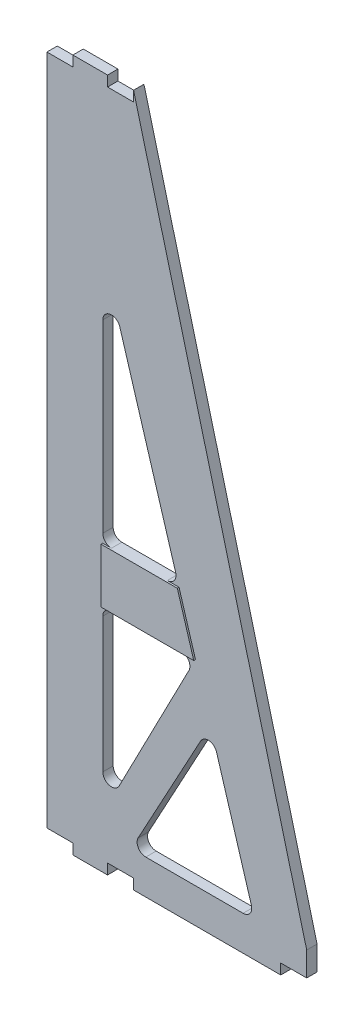
SolidWorks part; units mm, degrees
ref_plane "Plano frontal" through (0, 0, 0) normal (0, 0, 1) x (1, 0, 0)
ref_plane "Plano superior" through (0, 0, 0) normal (0, 1, 0) x (1, 0, 0)
ref_plane "Plano direito" through (0, 0, 0) normal (1, 0, 0) x (0, 0, -1)
sketch "Esboço2" plane through (0, 0, 0) normal (0, 0, 1) x (1, 0, 0)
  line L0 (0, 0) -> (0, 400)
  line L1 (0, 0) -> (150, 0)
  line L2 (150, 0) -> (150, 20)
  line L3 (0, 400) -> (50, 400)
  line L4 (50, 400) -> (150, 20)
extrude "Ressalto-extrusão1" add sketch "Esboço2" along normal blind 6
sketch "Esboço7" plane through (0, 0, 0) normal (0, 0, -1) x (-1, 0, 0)
  line L0 (-150, 20) -> (-120, 20) construction
  line L1 (-150, 0) -> (-150, 20) construction
  line L2 (-150, 20) -> (-50, 400) construction
  line L3 (0, 20) -> (-32.2764, 20) construction
  line L4 (0, 400) -> (0, 0) construction
  line L5 (-32.2764, 400) -> (-32.2764, 310) construction
  line L6 (-50, 400) -> (0, 400) construction
  line L7 (-32.2764, 20) -> (-32.2764, 310)
  line L8 (-120, 20) -> (-32.2764, 310)
  line L9 (-120, 20) -> (-32.2764, 20)
extrude "Corte-extrusão1" cut sketch "Esboço7" against normal through all
fillet "Filete1" radius 5 3 edges at (32.2764, 310, 3) (32.2764, 20, 3) (120, 20, 3)
ref_plane "Plano1" through (150, 0, 0) normal (1, 0, 0) x (0, 0, -1)
sketch "Esboço11" plane through (0, 0, 0) normal (0, 0, -1) x (-1, 0, 0)
  line L0 (-85.7903, 133.0918) -> (-32.2764, 133.0918)
  line L1 (-42.0622, 277.6496) -> (-118.0496, 26.4477) construction
  line L2 (-32.2764, 25) -> (-32.2764, 276.2019) construction
  line L3 (-32.2764, 133.0918) -> (-32.2764, 164.5313)
  line L4 (-32.2764, 164.5313) -> (-76.28, 164.5313)
  line L5 (-76.28, 164.5313) -> (-85.7903, 133.0918)
extrude "Ressalto-extrusão3" add sketch "Esboço11" against normal blind 7
sketch "Esboço12" plane through (0, 0, 0) normal (0, 0, -1) x (-1, 0, 0)
  line L0 (-85.7903, 133.0918) -> (-32.2764, 29.6572)
  line L1 (-32.2764, 25) -> (-32.2764, 133.0918) construction
  line L2 (-94.4687, 104.4022) -> (-48.6704, 20)
  line L3 (-85.7903, 133.0918) -> (-118.0496, 26.4477) construction
  line L4 (-113.2638, 20) -> (-37.2764, 20) construction
  line L5 (-48.6704, 20) -> (-27.5947, 20)
  line L6 (-27.5947, 20) -> (-32.2764, 29.6572)
  line L7 (-94.4687, 104.4022) -> (-85.7903, 133.0918)
extrude "Ressalto-extrusão4" add sketch "Esboço12" against normal blind 6
fillet "Filete2" radius 5 7 edges at (32.2764, 164.5313, 3) (76.28, 164.5313, 3) (32.2764, 133.0918, 3) (85.7903, 133.0918, 3) (32.2764, 29.6572, 3) (94.4687, 104.4022, 3) (48.6704, 20, 3)
sketch "Esboço13" plane through (0, 0, 6) normal (0, 0, 1) x (1, 0, 0)
  line L0 (50, 400) -> (0, 400) construction
  line L1 (0, 400) -> (15, 400)
  line L2 (0, 400) -> (0, 394)
  line L3 (0, 394) -> (15, 394)
  line L4 (15, 400) -> (15, 394)
  line L5 (50.0257, 400) -> (35.0257, 400)
  line L6 (50.0257, 400) -> (50.0257, 394)
  line L7 (50.0257, 394) -> (35.0257, 394)
  line L8 (35.0257, 400) -> (35.0257, 394)
extrude "Corte-extrusão2" cut sketch "Esboço13" against normal through all
sketch "Esboço15" plane through (0, 0, 6) normal (0, 0, 1) x (1, 0, 0)
  line L0 (15, 4.7267) -> (35, 4.7267) construction
  line L1 (0, 0) -> (15, 0)
  line L2 (0, 0) -> (0, 6)
  line L3 (0, 6) -> (15, 6)
  line L4 (15, 0) -> (15, 6)
  line L5 (0, 0) -> (150, 0) construction
  line L6 (35, 0) -> (50, 0)
  line L7 (35, 0) -> (35, 6)
  line L8 (35, 6) -> (50, 6)
  line L9 (50, 0) -> (50, 6)
  line L11 (150, 0) -> (135, 0)
  line L12 (150, 0) -> (150, 6)
  line L13 (150, 6) -> (135, 6)
  line L14 (135, 0) -> (135, 6)
extrude "Corte-extrusão3" cut sketch "Esboço15" against normal through all
